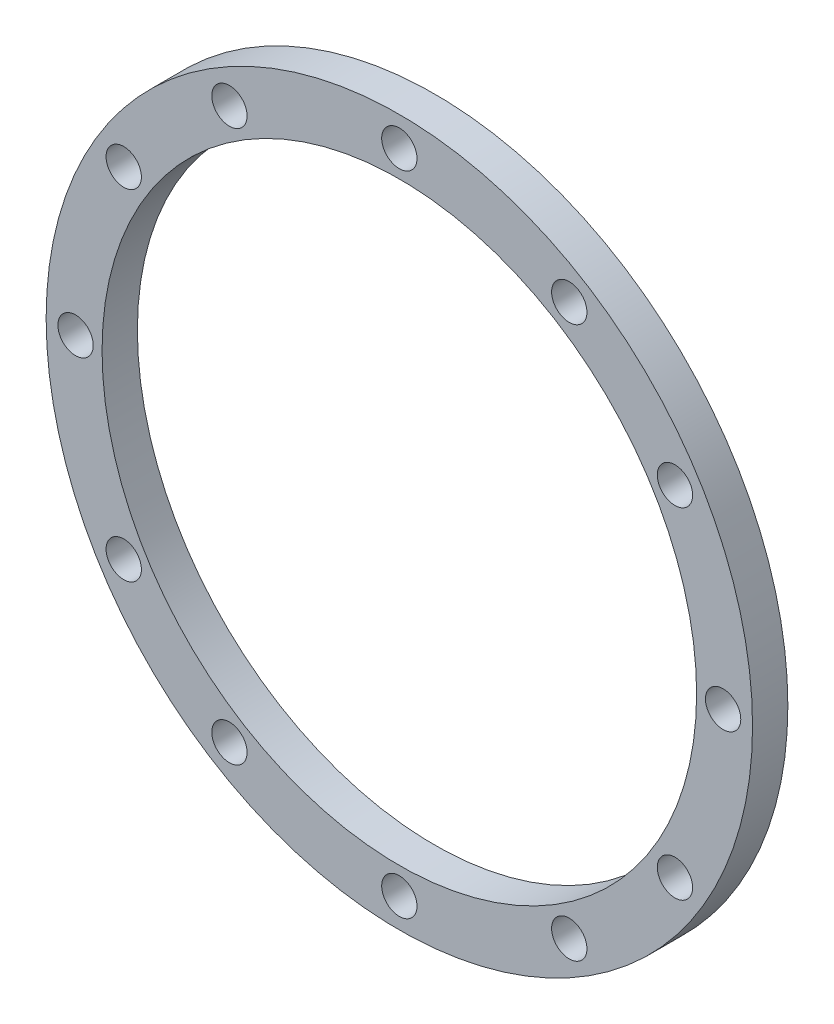
SolidWorks part; units mm, degrees
material "AISI 1020"
ref_plane "Ön Düzlem" through (0, 0, 0) normal (0, 0, 1) x (1, 0, 0)
ref_plane "Üst Düzlem" through (0, 0, 0) normal (0, 1, 0) x (1, 0, 0)
ref_plane "Sağ Düzlem" through (0, 0, 0) normal (1, 0, 0) x (0, 0, -1)
sketch "Çizim1" plane through (0, 0, 0) normal (0, 0, 1) x (1, 0, 0)
  circle A0 centre (0, 0) radius 252.5
  circle A1 centre (0, 0) radius 300
  dimension "D1" = 505
  dimension "D2" = 600
extrude "Yükseklik-Ekstrüzyon1" add sketch "Çizim1" along normal blind 30
sketch "Çizim2" plane through (0, 0, 30) normal (0, 0, 1) x (1, 0, 0)
  line L0 (-338.0724, 0) -> (366.2451, 0) construction
  line L1 (0, 389.8334) -> (0, -356.6891) construction
  circle A2 centre (0, 0) radius 275 construction
  circle A3 centre (0, 275) radius 15
  circle A4 centre (275, 0) radius 15
  circle A5 centre (-275, 0) radius 15
  circle A6 centre (0, -275) radius 15
  circle A7 centre (-144.3137, -234.0909) radius 15
  circle A8 centre (-234.0909, -144.3137) radius 15
  circle A9 centre (-234.0909, 144.3137) radius 15
  circle A10 centre (144.3137, -234.0909) radius 15
  circle A11 centre (234.0909, -144.3137) radius 15
  circle A12 centre (234.0909, 144.3137) radius 15
  circle A13 centre (-144.3137, 234.0909) radius 15
  circle A14 centre (144.3137, 234.0909) radius 15
  dimension "D1" = 550
  dimension "D2" = 30
  dimension "D3" = 150
  dimension "D4" = 150
  dimension "D5" = 150
  dimension "D6" = 150
  dimension "D7" = 150
  dimension "D8" = 150
  dimension "D9" = 150
  dimension "D10" = 150
extrude "Kes-Ekstrüzyon1" cut sketch "Çizim2" against normal blind 30
